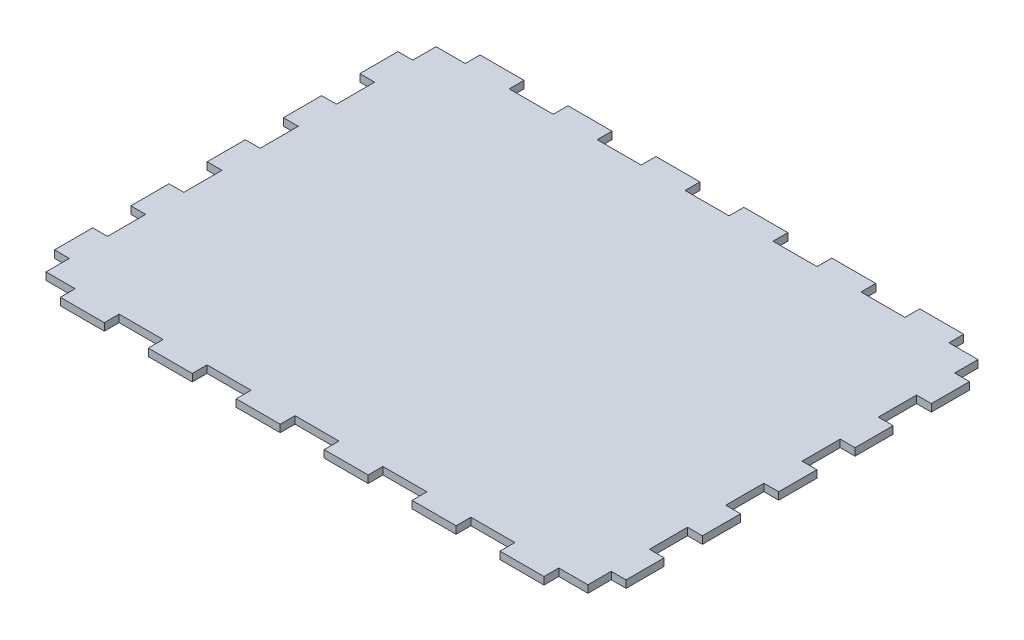
SolidWorks part; units mm, degrees
material "Balsa"
ref_plane "Front" through (0, 0, 0) normal (0, 0, 1) x (1, 0, 0)
ref_plane "Top" through (0, 0, 0) normal (0, 1, 0) x (1, 0, 0)
ref_plane "Right" through (0, 0, 0) normal (1, 0, 0) x (0, 0, -1)
sketch "Esboço1" plane through (0, 0, 0) normal (0, 1, 0) x (1, 0, 0)
  line L0 (-115.75, 85) -> (-97.75, 85) construction
  line L1 (115.75, -85) -> (-115.75, -85)
  line L2 (115.75, -85) -> (115.75, 85)
  line L3 (115.75, 85) -> (-115.75, 85)
  line L4 (-115.75, -85) -> (-115.75, 85)
  line L5 (115.75, -85) -> (-115.75, 85) construction
  line L6 (115.75, 85) -> (-115.75, -85) construction
  line L9 (115.75, -85) -> (97.75, -85) construction
  point P0 (0, 0)
  dimension "D1" = 231.5
  dimension "D2" = 170
extrude "Ressalto-extrusão1" add sketch "Esboço1" along normal blind 3
sketch "Esboço2" plane through (0, 0, 0) normal (0, -1, 0) x (1, 0, 0)
  line L0 (-80.13, 85) -> (-62.3223, 85)
  line L1 (-115.75, 85) -> (-97.9423, 85)
  line L2 (-115.75, 85) -> (-115.75, 79)
  line L3 (-115.75, 79) -> (-97.9423, 79)
  line L4 (-97.9423, 85) -> (-97.9423, 79)
  line L5 (-80.13, 85) -> (-80.13, 79)
  line L6 (-80.13, 79) -> (-62.3223, 79)
  line L7 (-62.3223, 85) -> (-62.3223, 79)
  line L8 (-44.51, 85) -> (-26.7023, 85)
  line L9 (-44.51, 85) -> (-44.51, 79)
  line L10 (-44.51, 79) -> (-26.7023, 79)
  line L11 (-26.7023, 85) -> (-26.7023, 79)
  line L12 (-8.89, 85) -> (8.9177, 85)
  line L13 (-8.89, 85) -> (-8.89, 79)
  line L14 (-8.89, 79) -> (8.9177, 79)
  line L15 (8.9177, 85) -> (8.9177, 79)
  line L16 (26.73, 85) -> (44.5377, 85)
  line L17 (26.73, 85) -> (26.73, 79)
  line L18 (26.73, 79) -> (44.5377, 79)
  line L19 (44.5377, 85) -> (44.5377, 79)
  line L20 (62.35, 85) -> (80.1577, 85)
  line L21 (62.35, 85) -> (62.35, 79)
  line L22 (62.35, 79) -> (80.1577, 79)
  line L23 (80.1577, 85) -> (80.1577, 79)
  line L24 (97.97, 85) -> (115.7777, 85)
  line L25 (97.97, 85) -> (97.97, 79)
  line L26 (97.97, 79) -> (115.7777, 79)
  line L27 (115.7777, 85) -> (115.7777, 79)
  line L28 (-80.13, -79) -> (-62.3223, -79)
  line L29 (-80.13, -79) -> (-80.13, -85)
  line L30 (-80.13, -85) -> (-62.3223, -85)
  line L31 (-62.3223, -79) -> (-62.3223, -85)
  line L32 (-44.51, -79) -> (-26.7023, -79)
  line L33 (-44.51, -79) -> (-44.51, -85)
  line L34 (-44.51, -85) -> (-26.7023, -85)
  line L35 (-26.7023, -79) -> (-26.7023, -85)
  line L36 (-8.89, -79) -> (8.9177, -79)
  line L37 (-8.89, -79) -> (-8.89, -85)
  line L38 (-8.89, -85) -> (8.9177, -85)
  line L39 (8.9177, -79) -> (8.9177, -85)
  line L40 (26.73, -79) -> (44.5377, -79)
  line L41 (26.73, -79) -> (26.73, -85)
  line L42 (26.73, -85) -> (44.5377, -85)
  line L43 (44.5377, -79) -> (44.5377, -85)
  line L44 (62.35, -79) -> (80.1577, -79)
  line L45 (62.35, -79) -> (62.35, -85)
  line L46 (62.35, -85) -> (80.1577, -85)
  line L47 (80.1577, -79) -> (80.1577, -85)
  line L48 (97.97, -79) -> (115.7777, -79)
  line L49 (97.97, -79) -> (97.97, -85)
  line L50 (97.97, -85) -> (115.7777, -85)
  line L51 (115.7777, -79) -> (115.7777, -85)
  line L52 (-115.75, -79) -> (-97.9423, -79)
  line L53 (-115.75, -79) -> (-115.75, -85)
  line L54 (-115.75, -85) -> (-97.9423, -85)
  line L55 (-97.9423, -79) -> (-97.9423, -85)
  dimension "D1" = 6
  dimension "D2" = 17.8077
  dimension "D3" = 7
  dimension "D4" = 2
extrude "Corte-extrusão1" cut sketch "Esboço2" against normal up to next
sketch "Esboço3" plane through (0, 0, 0) normal (0, -1, 0) x (1, 0, 0)
  line L0 (-115.75, 85) -> (-109.75, 85) construction
  line L1 (115.75, 85) -> (109.75, 85)
  line L2 (109.75, 69.5455) -> (109.75, 85)
  line L3 (-109.75, 85) -> (-115.75, 85)
  line L4 (-115.75, 69.5455) -> (-115.75, 85)
  line L7 (109.75, 69.5455) -> (115.75, 69.5455)
  line L8 (115.75, 85) -> (115.75, 69.5455)
  line L11 (-115.75, 69.5455) -> (-109.75, 69.5455)
  line L12 (-109.75, 85) -> (-109.75, 69.5455)
  line L13 (109.75, 85) -> (115.75, 85) construction
  line L14 (115.75, 54.09) -> (109.75, 54.09)
  line L15 (109.75, 38.6355) -> (109.75, 54.09)
  line L18 (109.75, 38.6355) -> (115.75, 38.6355)
  line L19 (115.75, 54.09) -> (115.75, 38.6355)
  line L20 (109.75, 54.09) -> (115.75, 54.09) construction
  line L21 (115.75, 23.18) -> (109.75, 23.18)
  line L22 (109.75, 7.7255) -> (109.75, 23.18)
  line L25 (109.75, 7.7255) -> (115.75, 7.7255)
  line L26 (115.75, 23.18) -> (115.75, 7.7255)
  line L27 (109.75, 23.18) -> (115.75, 23.18) construction
  line L28 (115.75, -7.73) -> (109.75, -7.73)
  line L29 (109.75, -23.1845) -> (109.75, -7.73)
  line L32 (109.75, -23.1845) -> (115.75, -23.1845)
  line L33 (115.75, -7.73) -> (115.75, -23.1845)
  line L34 (109.75, -7.73) -> (115.75, -7.73) construction
  line L35 (115.75, -38.64) -> (109.75, -38.64)
  line L36 (109.75, -54.0945) -> (109.75, -38.64)
  line L39 (109.75, -54.0945) -> (115.75, -54.0945)
  line L40 (115.75, -38.64) -> (115.75, -54.0945)
  line L41 (109.75, -38.64) -> (115.75, -38.64) construction
  line L42 (115.75, -69.55) -> (109.75, -69.55)
  line L43 (109.75, -85.0045) -> (109.75, -69.55)
  line L46 (109.75, -85.0045) -> (115.75, -85.0045)
  line L47 (115.75, -69.55) -> (115.75, -85.0045)
  line L48 (109.75, -69.55) -> (115.75, -69.55) construction
  line L49 (-109.75, 54.09) -> (-115.75, 54.09)
  line L50 (-115.75, 38.6355) -> (-115.75, 54.09)
  line L53 (-115.75, 38.6355) -> (-109.75, 38.6355)
  line L54 (-109.75, 54.09) -> (-109.75, 38.6355)
  line L55 (-115.75, 54.09) -> (-109.75, 54.09) construction
  line L56 (-109.75, 23.18) -> (-115.75, 23.18)
  line L57 (-115.75, 7.7255) -> (-115.75, 23.18)
  line L60 (-115.75, 7.7255) -> (-109.75, 7.7255)
  line L61 (-109.75, 23.18) -> (-109.75, 7.7255)
  line L62 (-115.75, 23.18) -> (-109.75, 23.18) construction
  line L63 (-109.75, -7.73) -> (-115.75, -7.73)
  line L64 (-115.75, -23.1845) -> (-115.75, -7.73)
  line L67 (-115.75, -23.1845) -> (-109.75, -23.1845)
  line L68 (-109.75, -7.73) -> (-109.75, -23.1845)
  line L69 (-115.75, -7.73) -> (-109.75, -7.73) construction
  line L70 (-109.75, -38.64) -> (-115.75, -38.64)
  line L71 (-115.75, -54.0945) -> (-115.75, -38.64)
  line L74 (-115.75, -54.0945) -> (-109.75, -54.0945)
  line L75 (-109.75, -38.64) -> (-109.75, -54.0945)
  line L76 (-115.75, -38.64) -> (-109.75, -38.64) construction
  line L77 (-109.75, -69.55) -> (-115.75, -69.55)
  line L78 (-115.75, -85.0045) -> (-115.75, -69.55)
  line L81 (-115.75, -85.0045) -> (-109.75, -85.0045)
  line L82 (-109.75, -69.55) -> (-109.75, -85.0045)
  line L83 (-115.75, -69.55) -> (-109.75, -69.55) construction
  point P0 (0, 0)
  dimension "D1" = 6
  dimension "D2" = 15.4545
  dimension "D3" = 2
  dimension "D4" = 6
extrude "Corte-extrusão2" cut sketch "Esboço3" against normal up to next
